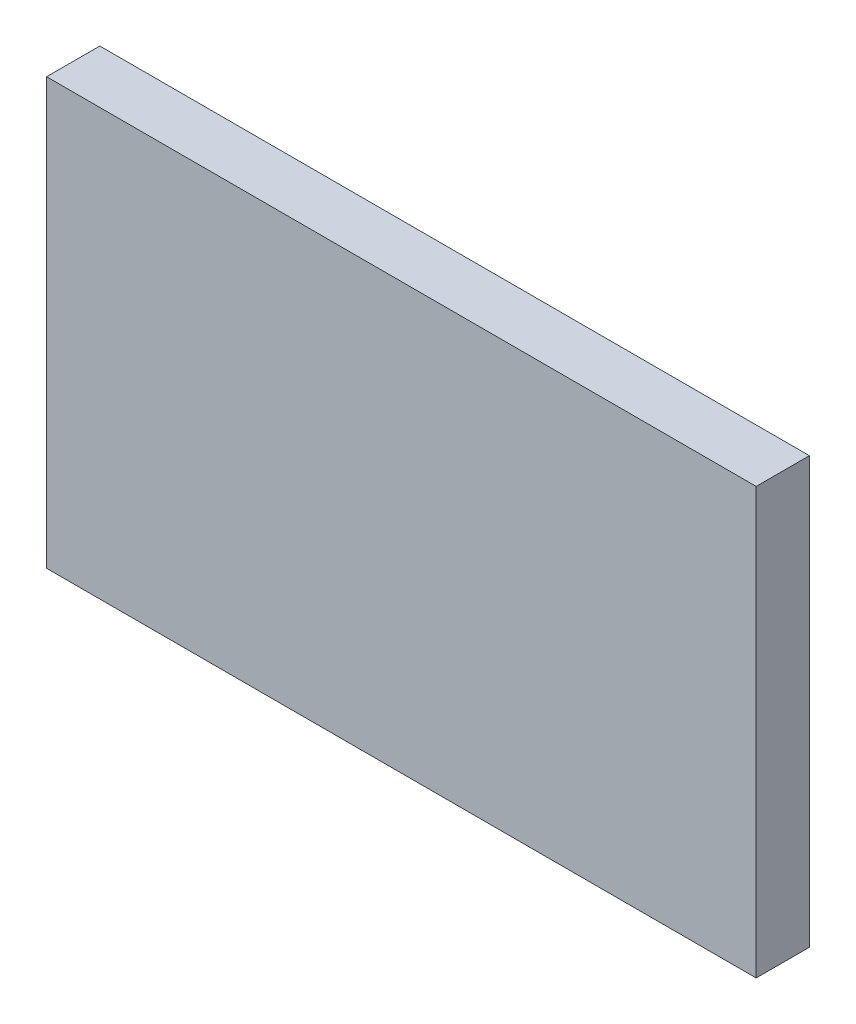
SolidWorks part; units mm, degrees
ref_plane "Front Plane" through (0, 0, 0) normal (0, 0, 1) x (1, 0, 0)
ref_plane "Top Plane" through (0, 0, 0) normal (0, 1, 0) x (1, 0, 0)
ref_plane "Right Plane" through (0, 0, 0) normal (1, 0, 0) x (0, 0, -1)
sketch "Sketch1" plane through (0, 0, 0) normal (0, 0, 1) x (1, 0, 0)
  line L1 (0, 0) -> (127, 0)
  line L2 (0, 0) -> (0, 76.2)
  line L3 (0, 76.2) -> (127, 76.2)
  line L4 (127, 0) -> (127, 76.2)
extrude "base" add sketch "Sketch1" along normal blind 9.525
